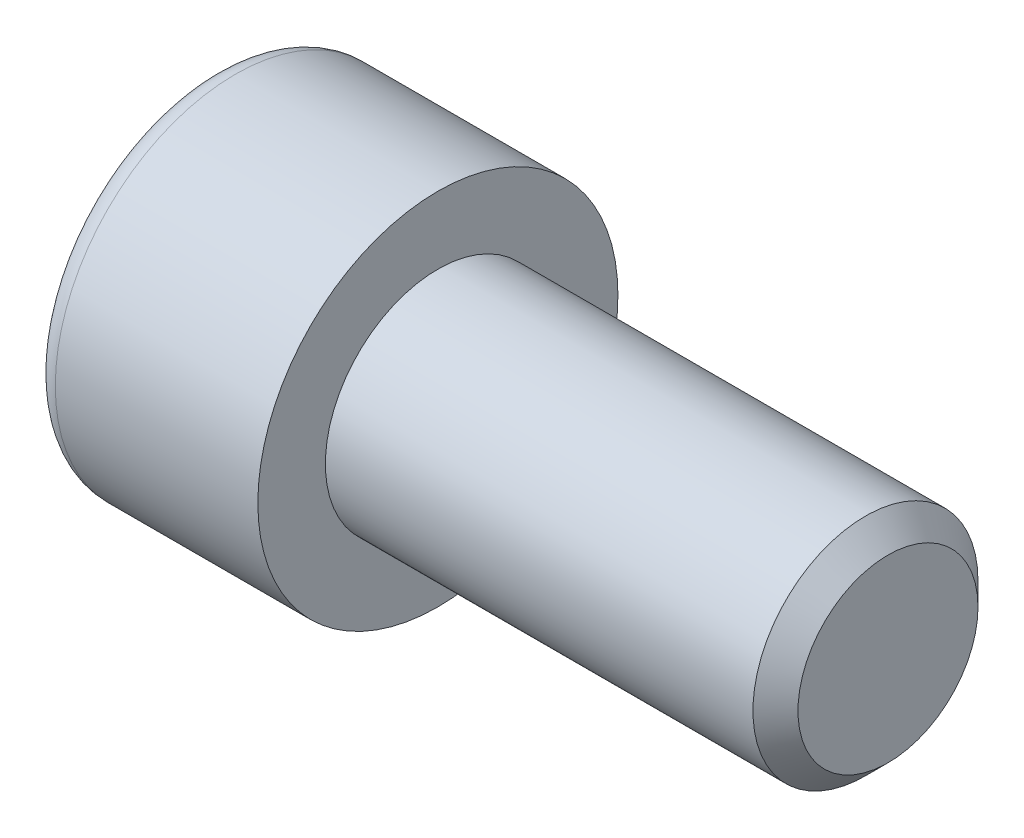
SolidWorks part; units mm, degrees
ref_plane "Спереди" through (0, 0, 0) normal (0, 0, 1) x (1, 0, 0)
ref_plane "Сверху" through (0, 0, 0) normal (0, 1, 0) x (1, 0, 0)
ref_plane "Справа" through (0, 0, 0) normal (1, 0, 0) x (0, 0, -1)
sketch "Эскиз1" plane through (0, 0, 0) normal (1, 0, 0) x (0, 0, -1)
  circle A0 centre (0, 0) radius 4
  dimension "D1" = 8
extrude "Вытянуть1" add sketch "Эскиз1" along normal blind 5
sketch "Эскиз2" plane through (5, 0, 0) normal (1, 0, 0) x (0, 0, -1)
  circle A0 centre (0, 0) radius 2.5
  dimension "D1" = 5
extrude "Вытянуть2" add sketch "Эскиз2" along normal blind 10
chamfer "Фаска1" distance 0.5 angle 45 1 edges at (15, 0, -2.5)
sketch "Эскиз3" plane through (0, 0, 0) normal (-1, 0, 0) x (0, 0, 1)
  line L0 (0, -2.3094) -> (0, 2.3094) construction
  line L1 (0, 2.3094) -> (-2, 1.1547)
  line L2 (-2, 1.1547) -> (-2, -1.1547)
  line L3 (-2, -1.1547) -> (0, -2.3094)
  line L4 (0, -2.3094) -> (2, -1.1547)
  line L5 (2, -1.1547) -> (2, 1.1547)
  line L6 (2, 1.1547) -> (0, 2.3094)
  circle A0 centre (0, 0) radius 2.3094
  dimension "D1" = 120
  dimension "D2" = 120
  dimension "D3" = 4
extrude "Вырез-Вытянуть1" cut sketch "Эскиз3" against normal blind 4 contours L1 L2 L3 L4 L5 L6
fillet "Скругление1" radius 1 6 edges at (4, 1.7321, 1) (4, 0, 2) (4, -1.7321, 1) (4, -1.7321, -1) (4, 0, -2) (4, 1.7321, -1)
fillet "Скругление2" radius 0.5 1 edges at (0, 0, -4)
